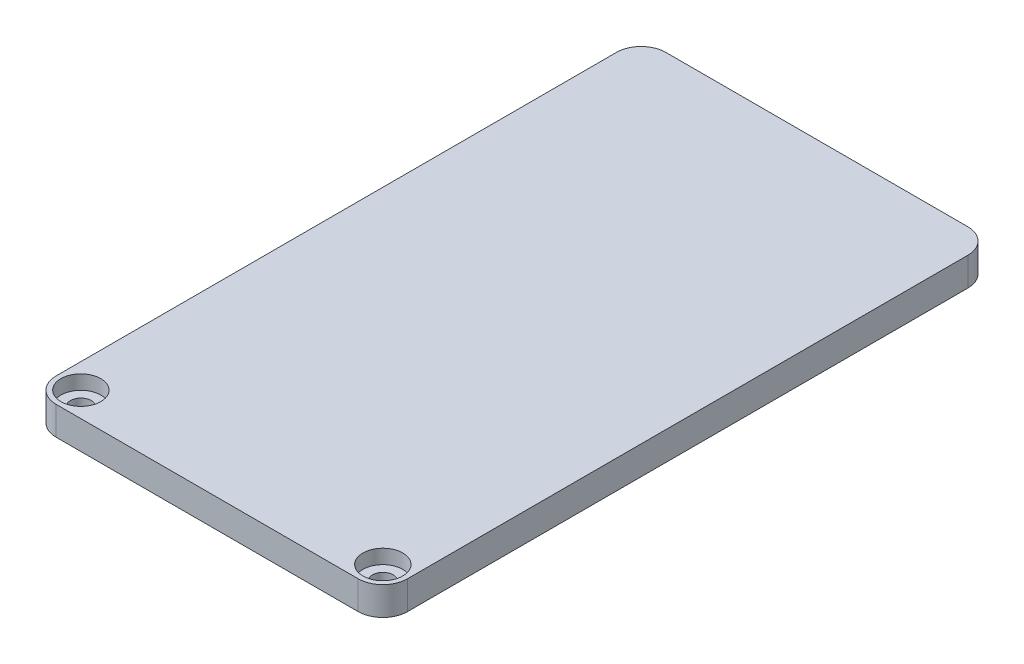
SolidWorks part; units mm, degrees
ref_plane "Płaszczyzna przednia" through (0, 0, 0) normal (0, 0, 1) x (1, 0, 0)
ref_plane "Płaszczyzna górna" through (0, 0, 0) normal (0, 1, 0) x (1, 0, 0)
ref_plane "Płaszczyzna prawa" through (0, 0, 0) normal (1, 0, 0) x (0, 0, -1)
sketch "Szkic1" plane through (0, 0, 0) normal (0, 1, 0) x (1, 0, 0)
  line L1 (-18.5, 32.1) -> (18.5, 32.1)
  line L2 (-18.5, 32.1) -> (-18.5, -32.1)
  line L3 (-18.5, -32.1) -> (18.5, -32.1)
  line L4 (18.5, 32.1) -> (18.5, -32.1)
  line L5 (-18.5, 32.1) -> (18.5, -32.1) construction
  line L6 (-18.5, -32.1) -> (18.5, 32.1) construction
  point P0 (0, 0)
  dimension "D1" = 37
  dimension "D2" = 64.2
extrude "Dodanie-wyciągnięcie1" add sketch "Szkic1" along normal blind 3
fillet "Zaokrąglenie1" radius 2.6 4 edges at (-18.5, 1.5, -32.1) (18.5, 1.5, -32.1) (-18.5, 1.5, 32.1) (18.5, 1.5, 32.1)
sketch "Szkic2" plane through (0, 3, 0) normal (0, 1, 0) x (1, 0, 0)
  line L1 (-15.9, -29.5) -> (15.9, -29.5) construction
  line L2 (-15.9, -29.5) -> (-15.9, 29.5) construction
  line L3 (-15.9, 29.5) -> (15.9, 29.5) construction
  line L4 (15.9, -29.5) -> (15.9, 29.5) construction
  line L5 (-15.9, -29.5) -> (15.9, 29.5) construction
  line L6 (-15.9, 29.5) -> (15.9, -29.5) construction
  circle A0 centre (15.9, -29.5) radius 1.1
  circle A1 centre (-15.9, -29.5) radius 1.1
  point P0 (0, 0)
  dimension "D3" = 2.2
  dimension "D4" = 2.2
  dimension "D1" = 59
  dimension "D2" = 31.8
extrude "Wytnij-wyciągnięcie1" cut sketch "Szkic2" against normal through all
sketch "Szkic3" plane through (0, 3, 0) normal (0, 1, 0) x (1, 0, 0)
  circle A0 centre (-15.9, -29.5) radius 2.1
  circle A1 centre (15.9, -29.5) radius 2.1
  dimension "D3" = 4.2
  dimension "D4" = 4.2
extrude "Wytnij-wyciągnięcie2" cut sketch "Szkic3" against normal blind 1.5
